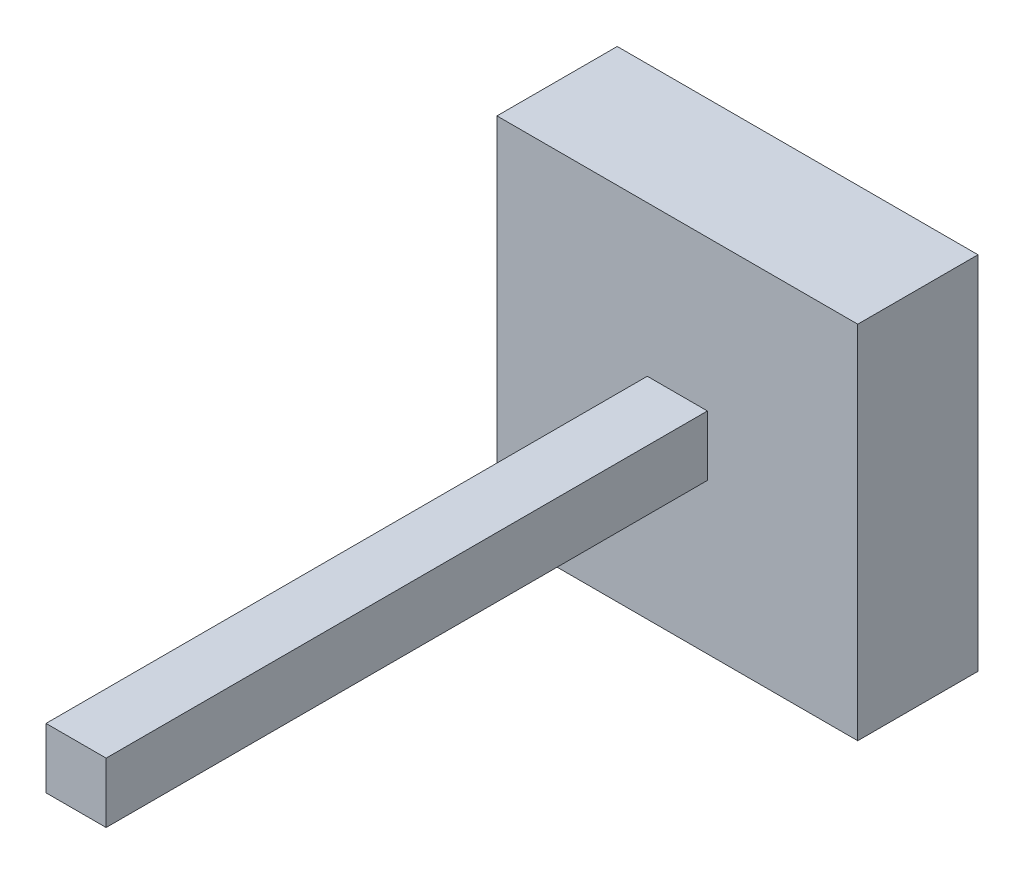
SolidWorks part; units mm, degrees
ref_plane "前视基准面" through (0, 0, 0) normal (0, 0, 1) x (1, 0, 0)
ref_plane "上视基准面" through (0, 0, 0) normal (0, 1, 0) x (1, 0, 0)
ref_plane "右视基准面" through (0, 0, 0) normal (1, 0, 0) x (0, 0, -1)
other "Configuration Table"
sketch "草图1" plane through (0, 0, 0) normal (0, 0, 1) x (1, 0, 0)
  line L1 (0, 0) -> (10, 0)
  line L2 (0, 0) -> (0, 10)
  line L3 (0, 10) -> (10, 10)
  line L4 (10, 0) -> (10, 10)
  dimension "D1" = 10
  dimension "D2" = 10
extrude "凸台-拉伸1" add sketch "草图1" along normal blind 100
sketch "草图2" plane through (0, 0, 0) normal (0, 0, -1) x (-1, 0, 0)
  line L0 (-10, 5) -> (0, 5) construction
  line L1 (-10, 0) -> (-10, 10) construction
  line L2 (0, 10) -> (0, 0) construction
  line L3 (-5, 10) -> (-5, 0) construction
  line L4 (-10, 10) -> (0, 10) construction
  line L5 (0, 0) -> (-10, 0) construction
  line L7 (-35, -25) -> (25, -25)
  line L8 (-35, -25) -> (-35, 35)
  line L9 (-35, 35) -> (25, 35)
  line L10 (25, -25) -> (25, 35)
  line L11 (-35, -25) -> (25, 35) construction
  line L12 (-35, 35) -> (25, -25) construction
  point P12 (-5, 5)
  dimension "D1" = 60
  dimension "D2" = 60
extrude "凸台-拉伸2" add sketch "草图2" along normal blind 20
